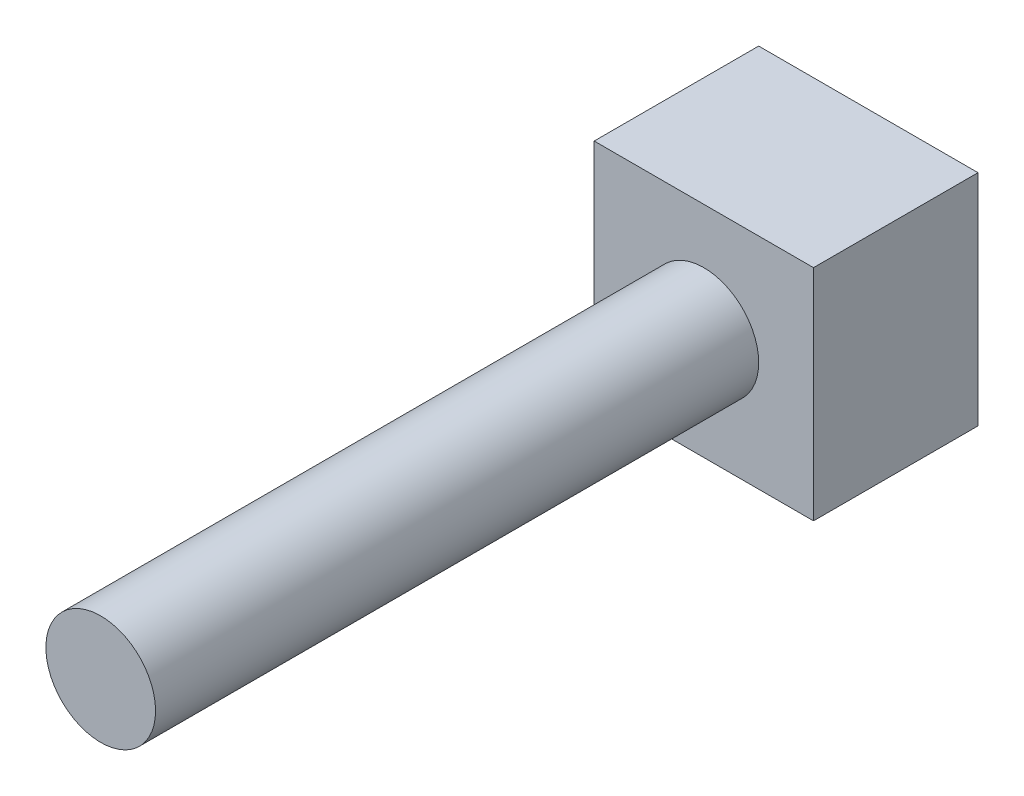
SolidWorks part; units mm, degrees
material "PE High Density"
ref_plane "Front Plane" through (0, 0, 0) normal (0, 0, 1) x (1, 0, 0)
ref_plane "Top Plane" through (0, 0, 0) normal (0, 1, 0) x (1, 0, 0)
ref_plane "Right Plane" through (0, 0, 0) normal (1, 0, 0) x (0, 0, -1)
sketch "Sketch1" plane through (0, 0, 0) normal (0, 0, 1) x (1, 0, 0)
  line L1 (-1, 1) -> (1, 1)
  line L2 (-1, 1) -> (-1, -1)
  line L3 (-1, -1) -> (1, -1)
  line L4 (1, 1) -> (1, -1)
  line L5 (-1, 1) -> (1, -1) construction
  line L6 (-1, -1) -> (1, 1) construction
  point P0 (0, 0)
  dimension "D1" = 2
  dimension "D2" = 2
extrude "Boss-Extrude1" add sketch "Sketch1" along normal blind 1.5
sketch "Sketch2" plane through (0, 0, 1.5) normal (0, 0, 1) x (1, 0, 0)
  circle A0 centre (0, 0) radius 0.5
  dimension "D1" = 1
extrude "Boss-Extrude2" add sketch "Sketch2" along normal blind 5.5
